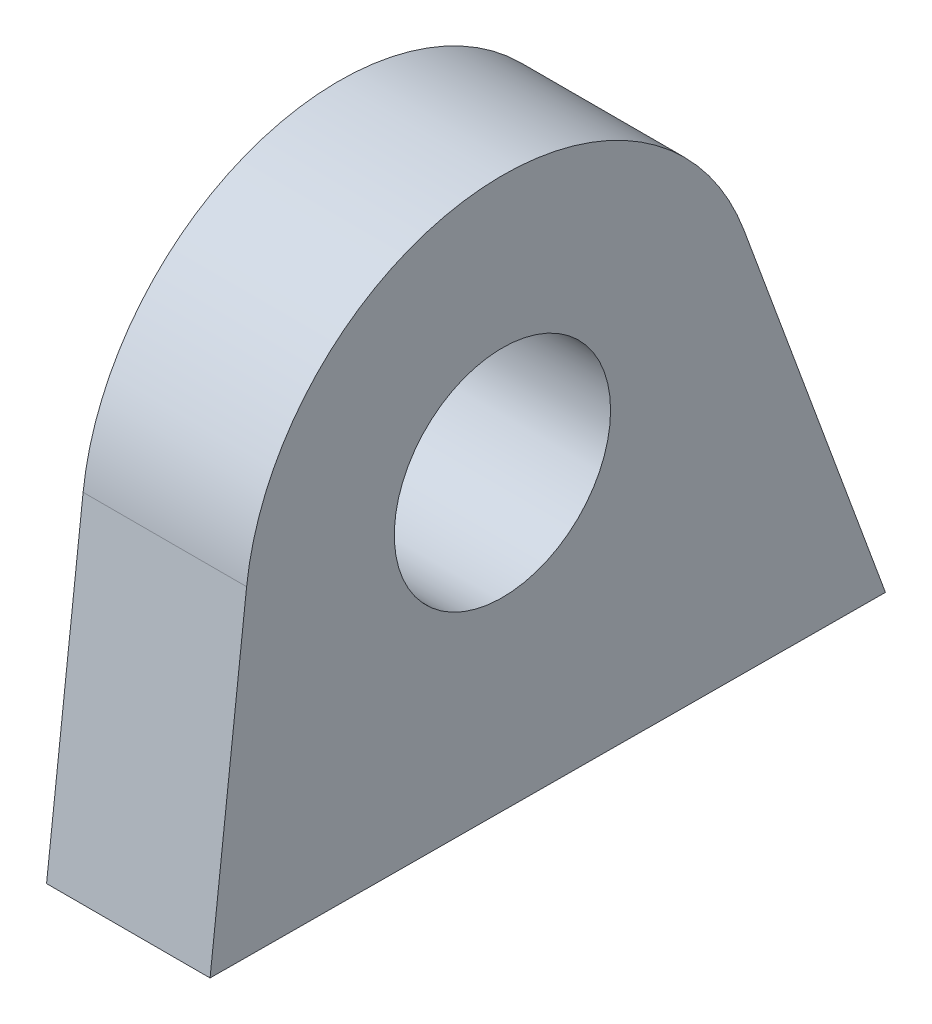
SolidWorks part; units mm, degrees
material "AISI 4130 Steel, normalized at 870C"
ref_plane "Front Plane" through (0, 0, 0) normal (0, 0, 1) x (1, 0, 0)
ref_plane "Top Plane" through (0, 0, 0) normal (0, 1, 0) x (1, 0, 0)
ref_plane "Right Plane" through (0, 0, 0) normal (1, 0, 0) x (0, 0, -1)
sketch "Sketch1" plane through (71.2924, 0, 0) normal (1, 0, 0) x (0, 0, -1)
  line L0 (916.7136, 360.6774) -> (922.2042, 345.7586)
  line L2 (897.3933, 358.3563) -> (895.9738, 345.9045)
  line L3 (895.9738, 345.9045) -> (922.2042, 345.7586)
  line L5 (916.7136, 360.6774) -> (927.0751, 332.5236) construction
  line L6 (894.4484, 332.5236) -> (897.3933, 358.3563) construction
  line L10 (1093.5736, 344.8049) -> (734.1704, 346.805) construction
  arc A0 (916.7136, 360.6774) -> (897.3933, 358.3563) centre (907.329, 357.2236) ccw
  circle A1 centre (907.329, 357.2236) radius 4.2
  point P4 (0, 0)
  point P6 (0, 0)
  dimension "D1" = 10
  dimension "D2" = 8.4
extrude "Boss-Extrude1" add sketch "Sketch1" along normal blind 6.35
